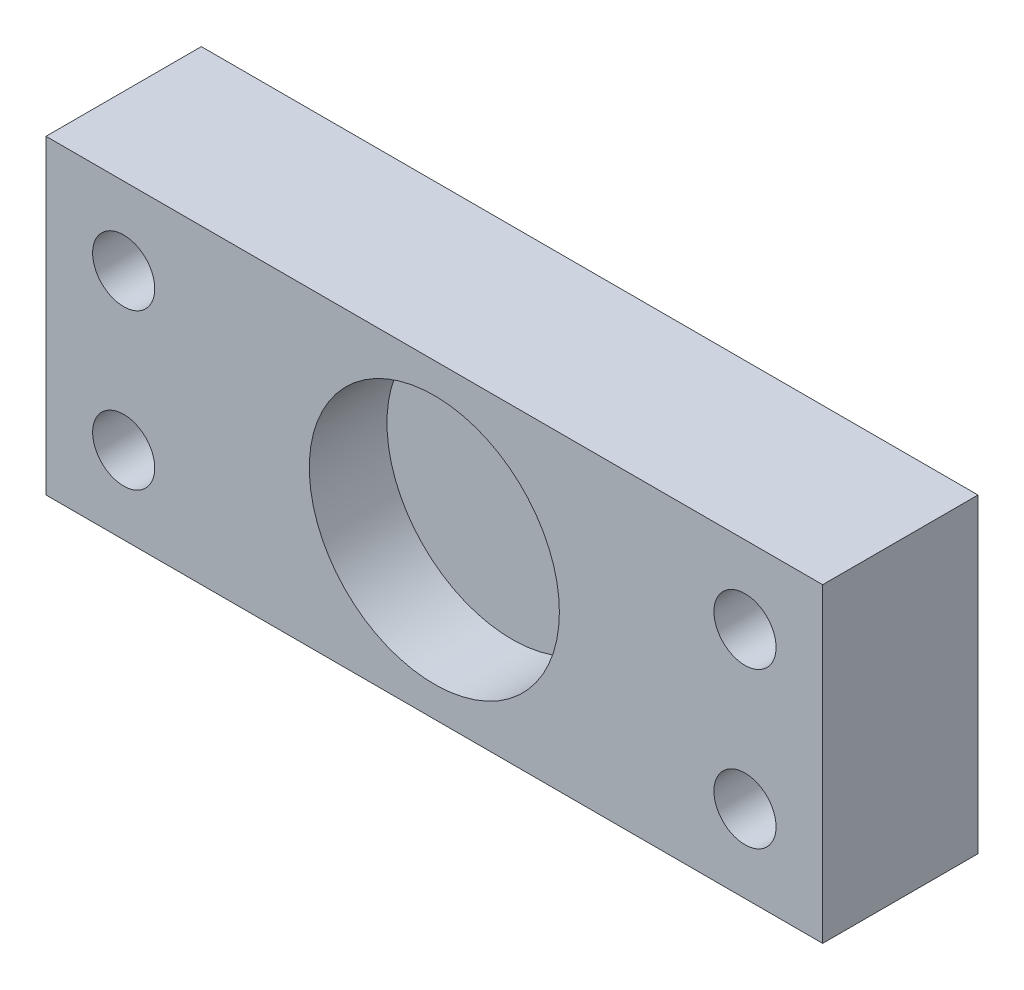
SolidWorks part; units mm, degrees
ref_plane "Front Plane" through (0, 0, 0) normal (0, 0, 1) x (1, 0, 0)
ref_plane "Top Plane" through (0, 0, 0) normal (0, 1, 0) x (1, 0, 0)
ref_plane "Right Plane" through (0, 0, 0) normal (1, 0, 0) x (0, 0, -1)
sketch "Sketch1" plane through (0, 0, 0) normal (0, 0, 1) x (1, 0, 0)
  line L1 (25, -10) -> (-25, -10)
  line L2 (25, -10) -> (25, 10)
  line L3 (25, 10) -> (-25, 10)
  line L4 (-25, -10) -> (-25, 10)
  line L5 (25, -10) -> (-25, 10) construction
  line L6 (25, 10) -> (-25, -10) construction
  point P0 (0, 0)
  dimension "D1" = 50
  dimension "D2" = 20
extrude "Boss-Extrude1" add sketch "Sketch1" along normal blind 10
sketch "Sketch3" plane through (0, 0, 10) normal (0, 0, 1) x (1, 0, 0)
  circle A0 centre (0, 0) radius 8.05
  dimension "D1" = 16.1
extrude "Cut-Extrude1" cut sketch "Sketch3" against normal blind 5
sketch "Sketch5" plane through (0, 0, 0) normal (0, 0, -1) x (-1, 0, 0)
  line L0 (-25, 10) -> (25, 10) construction
  line L1 (20, -5) -> (-20, -5) construction
  line L2 (20, -5) -> (20, 5) construction
  line L3 (20, 5) -> (-20, 5) construction
  line L4 (-20, -5) -> (-20, 5) construction
  line L5 (20, -5) -> (-20, 5) construction
  line L6 (20, 5) -> (-20, -5) construction
  line L7 (-25, -10) -> (-25, 10) construction
  circle A0 centre (-20, 5) radius 2
  circle A1 centre (-20, -5) radius 2
  circle A2 centre (20, 5) radius 2
  circle A3 centre (20, -5) radius 2
  point P0 (0, 0)
  dimension "D3" = 4
  dimension "D1" = 5
  dimension "D2" = 5
extrude "Cut-Extrude2" cut sketch "Sketch5" against normal blind 10
